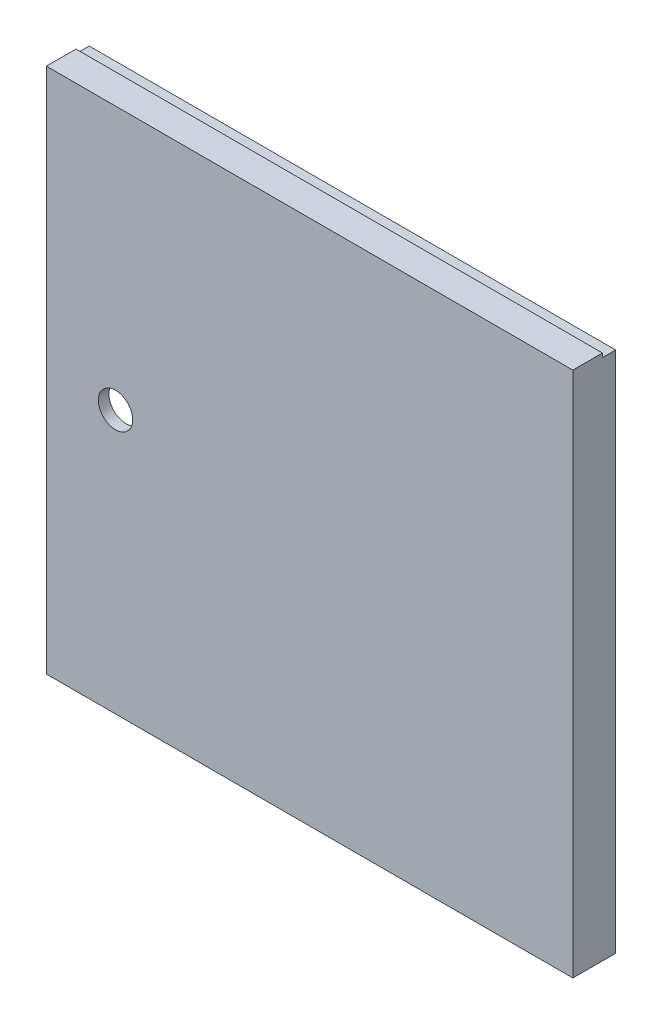
SolidWorks part; units mm, degrees
ref_plane "Front Plane" through (0, 0, 0) normal (0, 0, 1) x (1, 0, 0)
ref_plane "Top Plane" through (0, 0, 0) normal (0, 1, 0) x (1, 0, 0)
ref_plane "Right Plane" through (0, 0, 0) normal (1, 0, 0) x (0, 0, -1)
sketch "Sketch2" plane through (0, 0, 0) normal (0, 0, 1) x (1, 0, 0)
  line L1 (-50.8, -50.8) -> (50.8, -50.8)
  line L2 (-50.8, -50.8) -> (-50.8, 50.8)
  line L3 (-50.8, 50.8) -> (50.8, 50.8)
  line L4 (50.8, -50.8) -> (50.8, 50.8)
  line L5 (-50.8, -50.8) -> (50.8, 50.8) construction
  line L6 (-50.8, 50.8) -> (50.8, -50.8) construction
  point P0 (0, 0)
  dimension "D1" = 101.6
  dimension "D2" = 101.6
extrude "Boss-Extrude1" add sketch "Sketch2" along normal blind 8.255
sketch "Sketch3" plane through (0, 0, 0) normal (0, 0, -1) x (-1, 0, 0)
  line L0 (-48.768, -48.768) -> (48.768, -48.768)
  line L1 (-48.768, -48.768) -> (-48.768, 48.768)
  line L2 (48.768, -48.768) -> (48.768, 48.768)
  line L3 (-48.768, 48.768) -> (48.768, 48.768)
  line L4 (-48.768, -48.768) -> (48.768, 48.768) construction
  line L5 (48.768, -48.768) -> (-48.768, 48.768) construction
  line L6 (-50.8, 50.8) -> (50.8, 50.8) construction
  line L7 (50.8, 50.8) -> (50.8, -50.8) construction
  point P1 (0, 0)
  dimension "D1" = 2.032
  dimension "D2" = 2.032
extrude "Cut-Extrude1" cut sketch "Sketch3" against normal offset from surface (6.223 mm away) 2.032 up to face at (0, 0, 8.255)
sketch "Sketch4" plane through (0, 0, 8.255) normal (0, 0, 1) x (1, 0, 0)
  circle A0 centre (-37.4565, 0) radius 3.3111
  dimension "D1" = 6.6222
extrude "Cut-Extrude2" cut sketch "Sketch4" against normal blind 2.032
sketch "Sketch8" plane through (50.8, 0, 0) normal (1, 0, 0) x (0, 0, -1)
  line L1 (0, 50.8) -> (-2.54, 50.8)
  line L2 (0, 50.8) -> (0, 50.038)
  line L3 (0, 50.038) -> (-2.54, 50.038)
  line L4 (-2.54, 50.8) -> (-2.54, 50.038)
  dimension "D1" = 2.54
  dimension "D2" = 0.762
extrude "Cut-Extrude3" cut sketch "Sketch8" against normal through all
